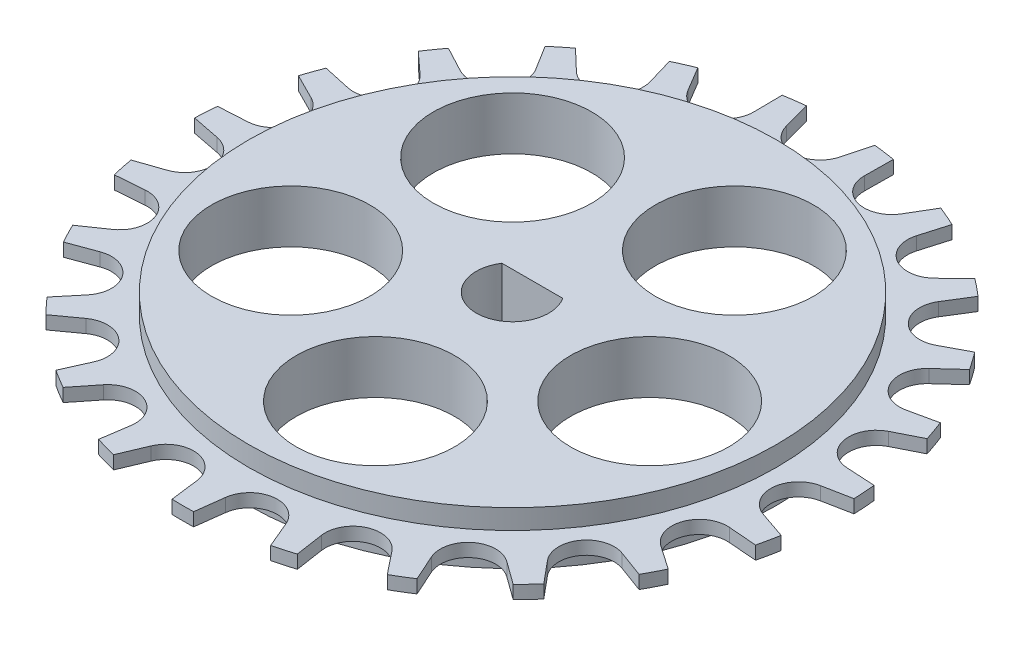
SolidWorks part; units mm, degrees
ref_plane "Ön Düzlem" through (0, 0, 0) normal (0, 0, 1) x (1, 0, 0)
ref_plane "Üst Düzlem" through (0, 0, 0) normal (0, 1, 0) x (1, 0, 0)
ref_plane "Sağ Düzlem" through (0, 0, 0) normal (1, 0, 0) x (0, 0, -1)
sketch "Çizim1" plane through (0, 0, 0) normal (0, 1, 0) x (1, 0, 0)
  circle A0 centre (0, 0) radius 50
  dimension "D1" = 100
extrude "Yükseklik-Ekstrüzyon1" add sketch "Çizim1" along normal blind 2
ref_plane "Düzlem1" through (0, 2, 0) normal (0, 1, 0) x (1, 0, 0)
sketch "Çizim2" plane through (0, 2, 0) normal (0, 1, 0) x (1, 0, 0)
  line L1 (-7.6683, 58.9959) -> (5.7368, 51.8006)
  line L3 (4.0564, 45.5407) -> (5.7368, 51.8006)
  line L4 (-4.0564, 45.5407) -> (-7.6683, 58.9959)
  arc A3 (-4.0564, 45.5407) -> (4.0564, 45.5407) centre (0, 46.6296) ccw
  dimension "D1" = 4.2
extrude "Kes-Ekstrüzyon2" cut sketch "Çizim2" against normal blind 2
pattern_circular "Dairesel Kaplama2" count 23 over 360 about axis through (0, 0, 0) along (0, 1, 0) of "Kes-Ekstrüzyon2"
sketch "Çizim12" plane through (0, 2, 0) normal (0, 1, 0) x (1, 0, 0)
  circle A0 centre (0, 0) radius 40
  dimension "D1" = 80
extrude "Yükseklik-Ekstrüzyon2" add sketch "Çizim12" along normal blind 3
sketch "Çizim13" plane through (0, 0, 0) normal (0, 1, 0) x (1, 0, 0)
  circle A0 centre (0, 0) radius 40
  dimension "D1" = 80
extrude "Yükseklik-Ekstrüzyon3" add sketch "Çizim13" against normal blind 3
sketch "Çizim14" plane through (0, 2, 0) normal (0, 1, 0) x (1, 0, 0)
  circle A2 centre (-17.6777, 17.6777) radius 12
  dimension "D2" = 24
extrude "Kes-Ekstrüzyon6" cut sketch "Çizim14" against normal mid plane 14
pattern_circular "Dairesel Kaplama5" count 5 over 360 about axis through (0, 0, 0) along (0, 1, 0) of "Kes-Ekstrüzyon6"
sketch "Çizim16" plane through (0, 2, 0) normal (0, 1, 0) x (1, 0, 0)
  line L1 (-4.6098, 3) -> (4.6098, 3)
  arc A0 (-4.6098, 3) -> (4.6098, 3) centre (0, 0) ccw
  dimension "D1" = 11
extrude "Kes-Ekstrüzyon7" cut sketch "Çizim16" against normal mid plane 14
